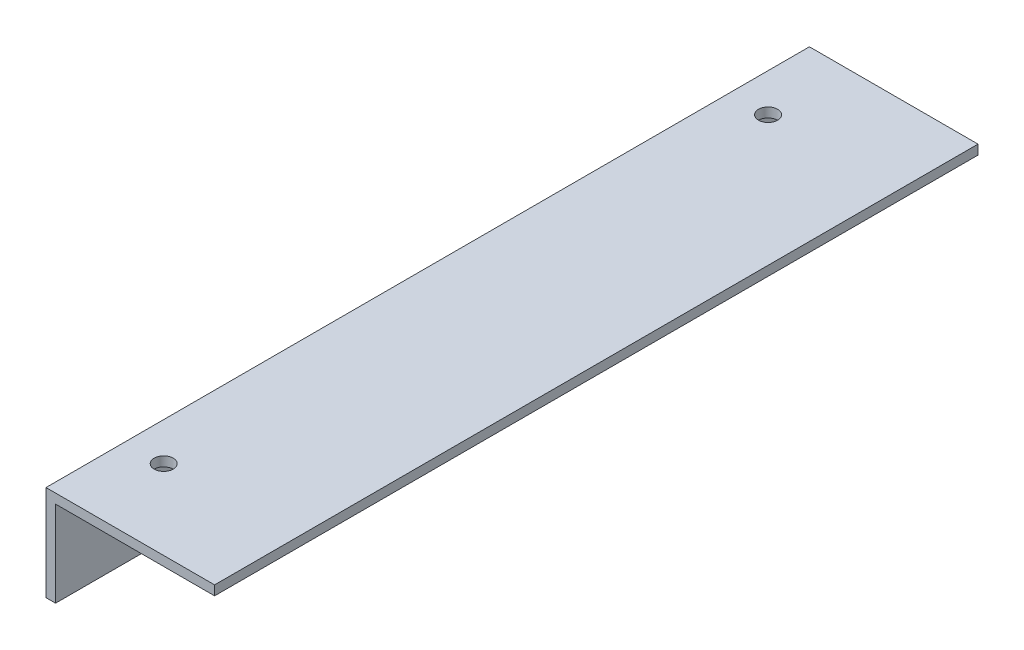
SolidWorks part; units mm, degrees
material "6061 合金"
ref_plane "前视基准面" through (0, 0, 0) normal (0, 0, 1) x (1, 0, 0)
ref_plane "上视基准面" through (0, 0, 0) normal (0, 1, 0) x (1, 0, 0)
ref_plane "右视基准面" through (0, 0, 0) normal (1, 0, 0) x (0, 0, -1)
sketch "草图1" plane through (0, 0, 0) normal (0, 0, 1) x (1, 0, 0)
  line L0 (0, 0) -> (26.5, 0)
  line L1 (26.5, 0) -> (26.5, -1.5)
  line L2 (26.5, -1.5) -> (1.5, -1.5)
  line L3 (1.5, -1.5) -> (1.5, -15)
  line L4 (1.5, -15) -> (0, -15)
  line L5 (0, -15) -> (0, 0)
  point P6 (1.5, -1.5)
  dimension "D1" = 25
  dimension "D2" = 15
  dimension "D3" = 1.5
extrude "凸台-拉伸1" add sketch "草图1" along normal blind 120
sketch "草图2" plane through (1.5, 0, 0) normal (1, 0, 0) x (0, 0, -1)
  line L0 (-120, -7.5) -> (0, -7.5) construction
  line L1 (-120, -15) -> (-120, -1.5) construction
  line L2 (0, -15) -> (0, -1.5) construction
  line L3 (-120, -15) -> (0, -15) construction
  circle A0 centre (-60, -7.5) radius 1.5
  circle A1 centre (-107, -7.5) radius 1.5
  circle A2 centre (-13, -7.5) radius 1.5
  dimension "D2" = 3
  dimension "D1" = 7.5
  dimension "D3" = 47
  dimension "D4" = 47
extrude "切除-拉伸1" cut sketch "草图2" against normal through all
sketch "草图3" plane through (0, 0, 0) normal (0, 1, 0) x (1, 0, 0)
  line L0 (0, -60) -> (26.5, -60) construction
  line L1 (0, -120) -> (0, 0) construction
  line L2 (26.5, -120) -> (26.5, 0) construction
  line L3 (6, 0) -> (6, -120) construction
  line L4 (26.5, 0) -> (0, 0) construction
  line L5 (26.5, -120) -> (0, -120) construction
  circle A0 centre (6, -107.5) radius 1.5
  circle A1 centre (6, -12.5) radius 1.5
  dimension "D1" = 3
  dimension "D2" = 47.5
  dimension "D3" = 6
extrude "切除-拉伸2" cut sketch "草图3" against normal through all
